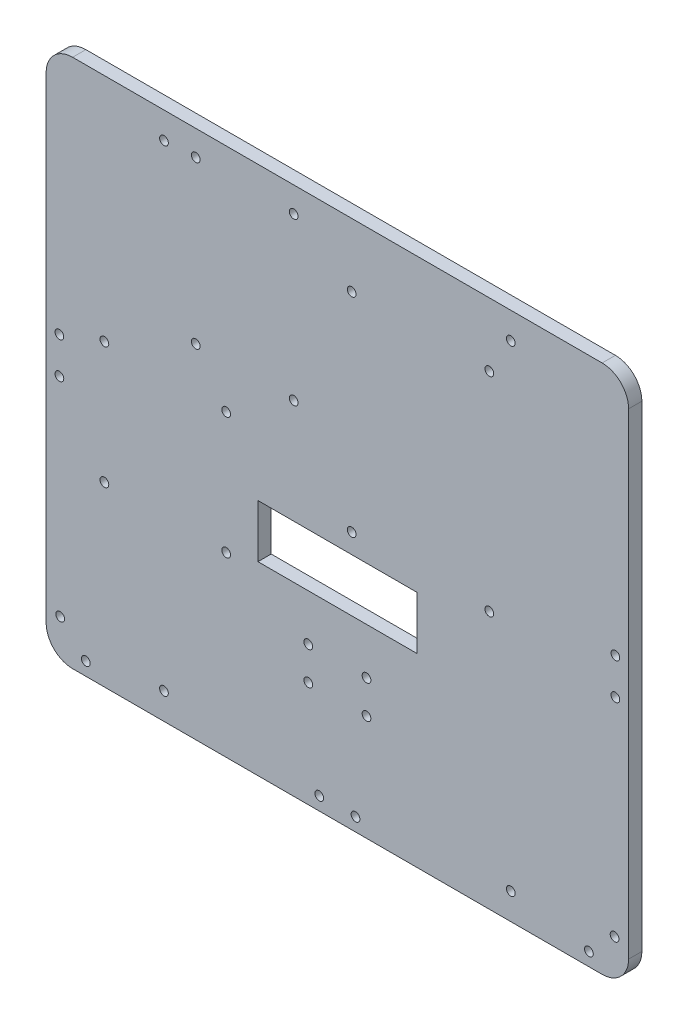
SolidWorks part; units mm, degrees
ref_plane "前视基准面" through (0, 0, 0) normal (0, 0, 1) x (1, 0, 0)
ref_plane "上视基准面" through (0, 0, 0) normal (0, 1, 0) x (1, 0, 0)
ref_plane "右视基准面" through (0, 0, 0) normal (1, 0, 0) x (0, 0, -1)
sketch "Model" plane through (0, 0, 0) normal (0, 0, 1) x (1, 0, 0)
  line L0 (196.3613, 321.4086) -> (396.3613, 321.4086)
  line L1 (406.3613, 311.4086) -> (406.3613, 131.4086)
  line L2 (396.3613, 121.4086) -> (196.3613, 121.4086)
  line L3 (186.3613, 131.4086) -> (186.3613, 311.4086)
  line L4 (266.3613, 211.4086) -> (326.3613, 211.4086)
  line L5 (326.3613, 211.4086) -> (326.3613, 191.4086)
  line L6 (326.3613, 191.4086) -> (266.3613, 191.4086)
  line L7 (266.3613, 191.4086) -> (266.3613, 211.4086)
  arc A0 (196.3613, 321.4086) -> (186.3613, 311.4086) centre (196.3613, 311.4086) ccw
  arc A1 (396.3613, 121.4086) -> (406.3613, 131.4086) centre (396.3613, 131.4086) ccw
  arc A2 (406.3613, 311.4086) -> (396.3613, 321.4086) centre (396.3613, 311.4086) ccw
  arc A3 (186.3613, 131.4086) -> (196.3613, 121.4086) centre (196.3613, 131.4086) ccw
  circle A4 centre (230.8613, 311.4086) radius 1.65
  circle A5 centre (361.8613, 311.4086) radius 1.65
  circle A6 centre (230.8613, 131.4086) radius 1.65
  circle A7 centre (361.8613, 131.4086) radius 1.65
  circle A8 centre (279.8613, 311.9086) radius 1.65
  circle A9 centre (279.8613, 250.9086) radius 1.65
  circle A10 centre (242.8613, 311.9086) radius 1.65
  circle A11 centre (242.8613, 250.9086) radius 1.65
  circle A12 centre (208.3613, 234.4086) radius 1.65
  circle A13 centre (254.3613, 234.4086) radius 1.65
  circle A14 centre (208.3613, 188.4086) radius 1.65
  circle A15 centre (254.3613, 188.4086) radius 1.65
  circle A16 centre (301.7613, 297.4086) radius 1.65
  circle A17 centre (301.7613, 218.8086) radius 1.65
  circle A18 centre (353.7613, 297.4086) radius 1.65
  circle A19 centre (353.7613, 218.8086) radius 1.65
  circle A20 centre (201.3613, 126.4086) radius 1.65
  circle A21 centre (191.6739, 136.0959) radius 1.65
  circle A22 centre (391.3613, 126.4086) radius 1.65
  circle A23 centre (401.0487, 136.0959) radius 1.65
  circle A24 centre (289.5113, 126.4086) radius 1.65
  circle A25 centre (303.2113, 126.4086) radius 1.65
  circle A26 centre (401.3613, 228.2586) radius 1.65
  circle A27 centre (401.3613, 214.5586) radius 1.65
  circle A28 centre (191.3613, 228.2586) radius 1.65
  circle A29 centre (191.3613, 214.5586) radius 1.65
  circle A30 centre (285.3613, 173.9086) radius 1.65
  circle A31 centre (307.3613, 173.9086) radius 1.65
  circle A32 centre (285.3613, 161.4086) radius 1.65
  circle A33 centre (307.3613, 161.4086) radius 1.65
extrude "凸台-拉伸1" add sketch "Model" along normal blind 5
